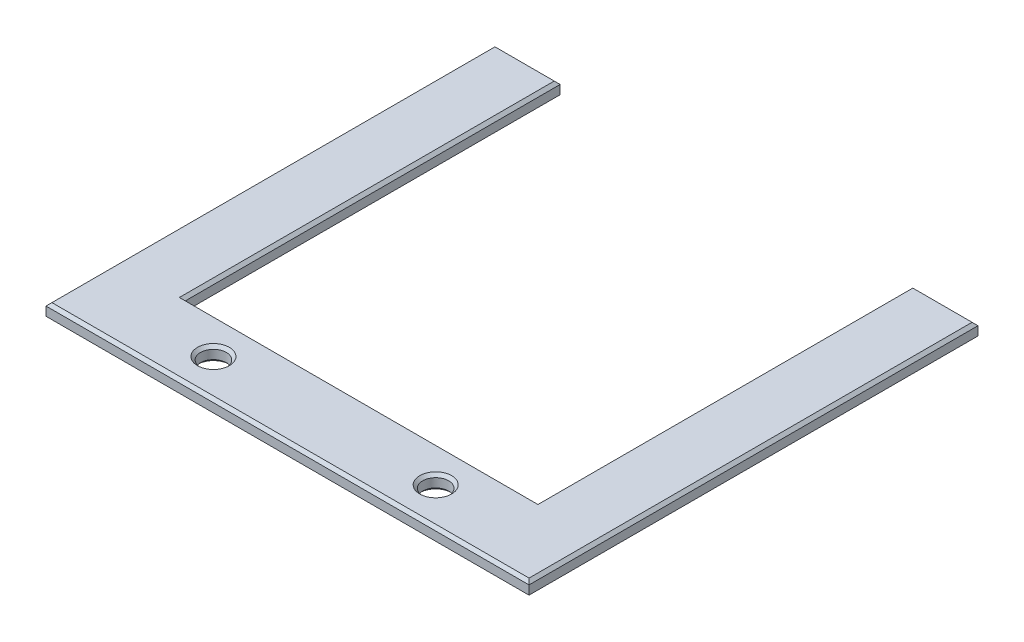
SolidWorks part; units mm, degrees
ref_plane "Front Plane" through (0, 0, 0) normal (0, 0, 1) x (1, 0, 0)
ref_plane "Top Plane" through (0, 0, 0) normal (0, 1, 0) x (1, 0, 0)
ref_plane "Right Plane" through (0, 0, 0) normal (1, 0, 0) x (0, 0, -1)
sketch "Sketch1" plane through (0, 0, 0) normal (0, 1, 0) x (1, 0, 0)
  line L0 (-32.6, 0) -> (32.6, 0)
  line L1 (32.6, 0) -> (32.6, 60.6)
  line L2 (32.6, 60.6) -> (23.8, 60.6)
  line L3 (23.8, 60.6) -> (23.8, 10)
  line L4 (23.8, 10) -> (-23.8, 10)
  line L5 (-23.8, 10) -> (-23.8, 60.6)
  line L6 (-23.8, 60.6) -> (-32.6, 60.6)
  line L7 (-32.6, 60.6) -> (-32.6, 0)
  line L8 (-15, 5) -> (15, 5) construction
  line L9 (0, 0) -> (0, 10) construction
  circle A0 centre (-15, 5) radius 1.75
  circle A1 centre (15, 5) radius 1.75
  point P11 (0, 5)
  dimension "D6" = 3.5
  dimension "D1" = 65.2
  dimension "D2" = 30
  dimension "D3" = 10
  dimension "D4" = 60.6
  dimension "D5" = 47.6
extrude "Boss-Extrude1" add sketch "Sketch1" along normal blind 2
chamfer "Chamfer1" distance 0.4 angle 45 20 edges at (15, 0, -3.25) (-15, 0, -3.25) (0, 0, 0) (32.6, 0, -30.3) (28.2, 0, -60.6) (23.8, 0, -35.3) (0, 0, -10) (-23.8, 0, -35.3) (-28.2, 0, -60.6) (-32.6, 0, -30.3) (15, 2, -3.25) (-28.2, 2, -60.6) (-23.8, 2, -35.3) (0, 2, -10) (23.8, 2, -35.3) (28.2, 2, -60.6) (32.6, 2, -30.3) (0, 2, 0) (-32.6, 2, -30.3) (-15, 2, -3.25)
